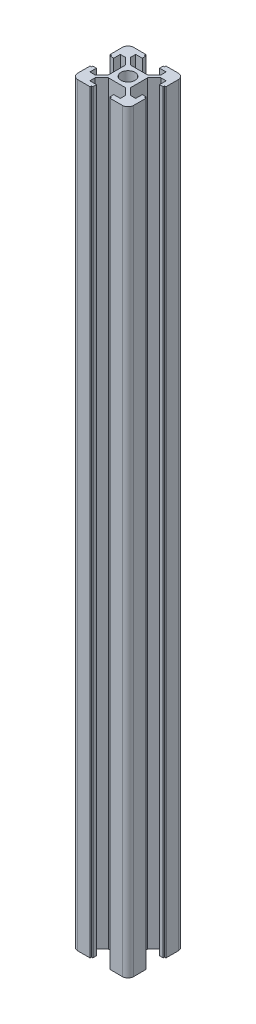
SolidWorks part; units mm, degrees
ref_plane "前视基准面" through (0, 0, 0) normal (0, 0, 1) x (1, 0, 0)
ref_plane "上视基准面" through (0, 0, 0) normal (0, 1, 0) x (1, 0, 0)
ref_plane "右视基准面" through (0, 0, 0) normal (1, 0, 0) x (0, 0, -1)
sketch "草图1" plane through (0, 0, 0) normal (0, 1, 0) x (1, 0, 0)
  line L0 (-6.2985, -5.45) -> (-3.9485, -3.1)
  line L1 (-5.45, -6.2985) -> (-3.1, -3.9485)
  line L2 (-6.2985, -5.45) -> (-8.2, -5.45)
  line L3 (-8.2, -5.45) -> (-8.2, -3.1)
  line L4 (-8.2, -3.1) -> (-10, -3.1)
  line L5 (-10, -3.1) -> (-10, -8)
  line L6 (-8, -10) -> (-3.1, -10)
  line L7 (-5.45, -6.2985) -> (-5.45, -8.2)
  line L8 (-5.45, -8.2) -> (-3.1, -8.2)
  line L9 (-3.1, -8.2) -> (-3.1, -10)
  line L10 (-3.9485, 0) -> (-3.9485, -3.1)
  line L11 (-3.1, -3.9485) -> (0, -3.9485)
  line L12 (-10, -3.6) -> (-9.5, -3.6)
  line L13 (-9.5, -3.6) -> (-9.5, -3.1)
  line L14 (-3.6, -10) -> (-3.6, -9.5)
  line L15 (-3.6, -9.5) -> (-3.1, -9.5)
  line L16 (-3.9485, 0) -> (-2.5, 0) construction
  line L17 (0, -2.5) -> (0, -3.9485) construction
  line L18 (-5.45, 6.2985) -> (-3.1, 3.9485)
  line L19 (-6.2985, 5.45) -> (-3.9485, 3.1)
  line L20 (-5.45, 6.2985) -> (-5.45, 8.2)
  line L21 (-5.45, 8.2) -> (-3.1, 8.2)
  line L22 (-3.1, 8.2) -> (-3.1, 10)
  line L23 (-3.1, 10) -> (-8, 10)
  line L24 (-10, 8) -> (-10, 3.1)
  line L25 (-6.2985, 5.45) -> (-8.2, 5.45)
  line L26 (-8.2, 5.45) -> (-8.2, 3.1)
  line L27 (-8.2, 3.1) -> (-10, 3.1)
  line L28 (-3.1, 3.9485) -> (0, 3.9485)
  line L29 (-3.9485, 3.1) -> (-3.9485, 0)
  line L30 (-3.6, 10) -> (-3.6, 9.5)
  line L31 (-3.6, 9.5) -> (-3.1, 9.5)
  line L32 (-10, 3.6) -> (-9.5, 3.6)
  line L33 (-9.5, 3.6) -> (-9.5, 3.1)
  line L34 (0, 3.9485) -> (0, 2.5) construction
  line L35 (-2.5, 0) -> (-3.9485, 0) construction
  line L36 (6.2985, 5.45) -> (3.9485, 3.1)
  line L37 (5.45, 6.2985) -> (3.1, 3.9485)
  line L38 (6.2985, 5.45) -> (8.2, 5.45)
  line L39 (8.2, 5.45) -> (8.2, 3.1)
  line L40 (8.2, 3.1) -> (10, 3.1)
  line L41 (10, 3.1) -> (10, 8)
  line L42 (8, 10) -> (3.1, 10)
  line L43 (5.45, 6.2985) -> (5.45, 8.2)
  line L44 (5.45, 8.2) -> (3.1, 8.2)
  line L45 (3.1, 8.2) -> (3.1, 10)
  line L46 (3.9485, 0) -> (3.9485, 3.1)
  line L47 (3.1, 3.9485) -> (0, 3.9485)
  line L48 (10, 3.6) -> (9.5, 3.6)
  line L49 (9.5, 3.6) -> (9.5, 3.1)
  line L50 (3.6, 10) -> (3.6, 9.5)
  line L51 (3.6, 9.5) -> (3.1, 9.5)
  line L52 (3.9485, 0) -> (2.5, 0) construction
  line L53 (0, 2.5) -> (0, 3.9485) construction
  line L54 (5.45, -6.2985) -> (3.1, -3.9485)
  line L55 (6.2985, -5.45) -> (3.9485, -3.1)
  line L56 (5.45, -6.2985) -> (5.45, -8.2)
  line L57 (5.45, -8.2) -> (3.1, -8.2)
  line L58 (3.1, -8.2) -> (3.1, -10)
  line L59 (3.1, -10) -> (8, -10)
  line L60 (10, -8) -> (10, -3.1)
  line L61 (6.2985, -5.45) -> (8.2, -5.45)
  line L62 (8.2, -5.45) -> (8.2, -3.1)
  line L63 (8.2, -3.1) -> (10, -3.1)
  line L64 (0, -3.9485) -> (3.1, -3.9485)
  line L65 (3.9485, -3.1) -> (3.9485, 0)
  line L66 (3.6, -10) -> (3.6, -9.5)
  line L67 (3.6, -9.5) -> (3.1, -9.5)
  line L68 (10, -3.6) -> (9.5, -3.6)
  line L69 (9.5, -3.6) -> (9.5, -3.1)
  line L70 (0, -3.9485) -> (0, -2.5) construction
  line L71 (2.5, 0) -> (3.9485, 0) construction
  line L72 (0, 3.9485) -> (-3.1, 3.9485) [skipped]
  circle A0 centre (0, 0) radius 2.5
  arc A1 (-10, -8) -> (-8, -10) centre (-8, -8) ccw
  arc A3 (-8, 10) -> (-10, 8) centre (-8, 8) ccw
  arc A5 (10, 8) -> (8, 10) centre (8, 8) ccw
  arc A7 (8, -10) -> (10, -8) centre (8, -8) ccw
  point P25 (-10, -10)
  point P98 (0, 0)
  dimension "D9" = 2
  dimension "D15" = 5
  dimension "D2" = 1.2
  dimension "D4" = 5.45
  dimension "D5" = 1.8
  dimension "D6" = 3.1
  dimension "D7" = 135
  dimension "D10" = 0.5
  dimension "D11" = 0.5
  dimension "D12" = 0.5
  dimension "D13" = 0.5
  dimension "D14" = 4
extrude "凸台-拉伸1" add sketch "草图1" along normal blind 270 contours L59 A7 L60 L68 L69 L63 L62 L61 L55 L65 L46 L36 L38 L39 L40 L49 L48 L41 A5 L42 L50 L51 L45 L44 L43 L37 L47 L28 L18 L20 L21 L22 L31 L30 L23 A3 L24 L32 L33 L27 L26 L25 L19 L29 L10 L0 L2 L3 L4 L13 L12
